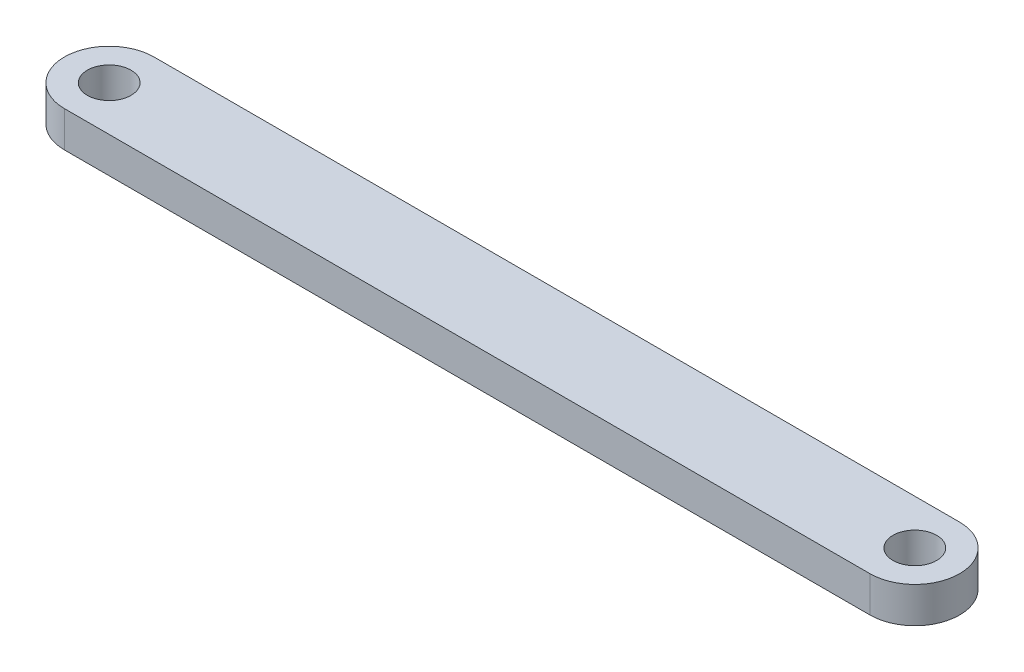
SolidWorks part; units mm, degrees
ref_plane "Front Plane" through (0, 0, 0) normal (0, 0, 1) x (1, 0, 0)
ref_plane "Top Plane" through (0, 0, 0) normal (0, 1, 0) x (1, 0, 0)
ref_plane "Right Plane" through (0, 0, 0) normal (1, 0, 0) x (0, 0, -1)
sketch "Sketch1" plane through (0, 0, 0) normal (0, 1, 0) x (1, 0, 0)
  line L5 (-25.3394, -3.799) -> (25.4606, 3.8172) construction
  line L6 (-25.3394, 3.8172) -> (25.2188, -3.799) construction
  line L9 (-3.1144, 3.1831) -> (54.0356, 3.1831)
  line L10 (-3.1144, -3.1669) -> (54.0356, -3.1669)
  circle A0 centre (-3.1144, 0.0081) radius 1.55
  circle A1 centre (54.0356, 0.0081) radius 1.55
  arc A2 (-3.1144, 3.1831) -> (-3.1144, -3.1669) centre (-3.1144, 0.0081) ccw
  arc A3 (54.0356, -3.1669) -> (54.0356, 3.1831) centre (54.0356, 0.0081) ccw
  arc A4 (0.0605, -0.0091) -> (0.0606, 0.0091) centre (-3.1144, 0.0081) ccw
  point P0 (0, 0)
  dimension "D3" = 3.1
  dimension "D4" = 57.15
  dimension "D7" = 6.35
  dimension "D8" = 3.1
  dimension "D9" = 6.35
  dimension "D2" = 7.62
extrude "Boss-Extrude2" add sketch "Sketch1" along normal blind 2.54
